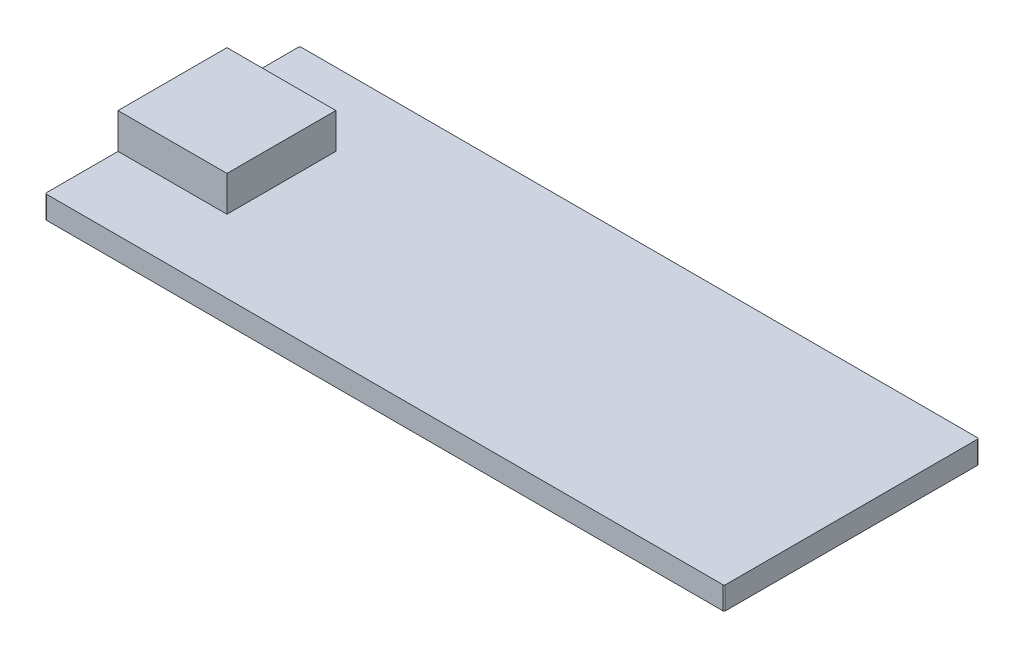
SolidWorks part; units mm, degrees
ref_plane "Front Plane" through (0, 0, 0) normal (0, 0, 1) x (1, 0, 0)
ref_plane "Top Plane" through (0, 0, 0) normal (0, 1, 0) x (1, 0, 0)
ref_plane "Right Plane" through (0, 0, 0) normal (1, 0, 0) x (0, 0, -1)
sketch "Sketch1" plane through (0, 0, 0) normal (0, 1, 0) x (1, 0, 0)
  line L1 (-24, 9) -> (24, 9)
  line L2 (-24, 9) -> (-24, -9)
  line L3 (-24, -9) -> (24, -9)
  line L4 (24, 9) -> (24, -9)
  line L5 (-24, 9) -> (24, -9) construction
  line L6 (-24, -9) -> (24, 9) construction
  point P0 (0, 0)
  dimension "D1" = 48
  dimension "D2" = 18
extrude "Boss-Extrude1" add sketch "Sketch1" along normal mid plane 1.6
fillet "Fillet1" radius 0.1 4 edges at (-24, 0, 9) (24, 0, 9) (24, 0, -9) (-24, 0, -9)
sketch "Sketch2" plane through (0, 0.8, 0) normal (0, 1, 0) x (1, 0, 0)
  line L0 (23.9, 9) -> (-23.9, 9) construction
  line L1 (-24, 8.9) -> (-24, -8.9) construction
  circle A0 centre (-22.62, 7.62) radius 0.825
  circle A3 centre (-22.62, -7.62) radius 0.825
  circle A4 centre (18.02, -7.62) radius 0.825 [skipped]
  circle A5 centre (18.02, 7.62) radius 0.825 [skipped]
  circle A6 centre (-20.08, 7.62) radius 0.825
  circle A7 centre (-20.08, -7.62) radius 0.825
  circle A8 centre (-17.54, 7.62) radius 0.825
  circle A9 centre (-17.54, -7.62) radius 0.825
  circle A10 centre (-15, 7.62) radius 0.825
  circle A11 centre (-15, -7.62) radius 0.825
  circle A12 centre (-12.46, 7.62) radius 0.825
  circle A13 centre (-12.46, -7.62) radius 0.825
  circle A14 centre (-9.92, 7.62) radius 0.825
  circle A15 centre (-9.92, -7.62) radius 0.825
  circle A16 centre (-7.38, 7.62) radius 0.825
  circle A17 centre (-7.38, -7.62) radius 0.825
  circle A18 centre (-4.84, 7.62) radius 0.825
  circle A19 centre (-4.84, -7.62) radius 0.825
  circle A20 centre (-2.3, 7.62) radius 0.825
  circle A21 centre (-2.3, -7.62) radius 0.825
  circle A22 centre (0.24, 7.62) radius 0.825
  circle A23 centre (0.24, -7.62) radius 0.825
  circle A24 centre (2.78, 7.62) radius 0.825
  circle A25 centre (2.78, -7.62) radius 0.825
  circle A26 centre (5.32, 7.62) radius 0.825
  circle A27 centre (5.32, -7.62) radius 0.825
  circle A28 centre (7.86, 7.62) radius 0.825
  circle A29 centre (7.86, -7.62) radius 0.825
  circle A30 centre (10.4, 7.62) radius 0.825
  circle A31 centre (10.4, -7.62) radius 0.825
  circle A32 centre (12.94, 7.62) radius 0.825
  circle A33 centre (12.94, -7.62) radius 0.825
  circle A34 centre (15.48, 7.62) radius 0.825
  circle A35 centre (15.48, -7.62) radius 0.825
  dimension "D1" = 1.65
  dimension "D2" = 1.38
  dimension "D3" = 1.38
  dimension "D4" = 2
  dimension "D5" = 2
  dimension "D6" = 16
sketch "Sketch3" plane through (0, 0.8, 0) normal (0, 1, 0) x (1, 0, 0)
  line L0 (-2.255, 0) -> (2.255, 0) construction
  line L1 (-24, 3.85) -> (-16.3, 3.85)
  line L2 (-24, 3.85) -> (-24, -3.85)
  line L3 (-24, -3.85) -> (-16.3, -3.85)
  line L4 (-16.3, 3.85) -> (-16.3, -3.85)
  line L5 (-24, 3.85) -> (-16.3, -3.85) construction
  line L6 (-24, -3.85) -> (-16.3, 3.85) construction
  line L7 (-24, 8.9) -> (-24, -8.9) construction
  point P0 (-20.15, 0)
  dimension "D1" = 0
  dimension "D2" = 7.7
  dimension "D3" = 7.7
extrude "Boss-Extrude2" add sketch "Sketch3" along normal blind 2.5
ref_plane "Plane1" through (0, -3.3, 0) normal (0, -1, 0) x (-1, 0, 0)
